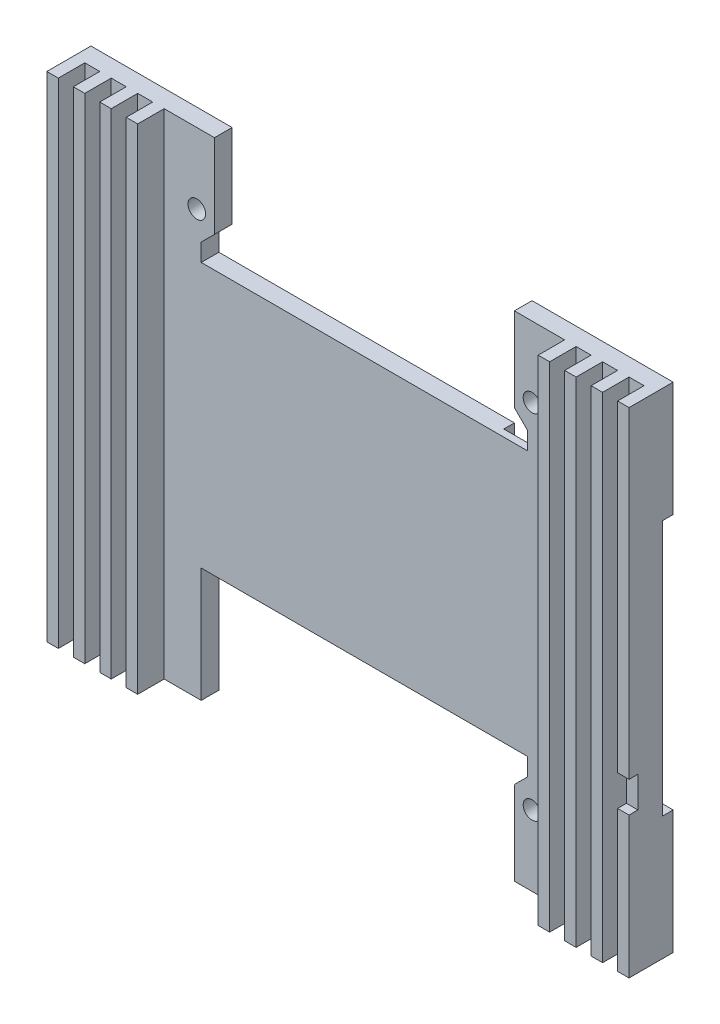
SolidWorks part; units mm, degrees
ref_plane "前视基准面" through (0, 0, 0) normal (0, 0, 1) x (1, 0, 0)
ref_plane "上视基准面" through (0, 0, 0) normal (0, 1, 0) x (1, 0, 0)
ref_plane "右视基准面" through (0, 0, 0) normal (1, 0, 0) x (0, 0, -1)
other "Configuration Table"
sketch "草图1" plane through (0, 0, 0) normal (0, 0, 1) x (1, 0, 0)
  line L0 (-18.5, 15) -> (18.5, 15)
  line L1 (18.5, 15) -> (18.5, 17)
  line L2 (18.5, 17) -> (17, 18.5)
  line L3 (17, 18.5) -> (17, 28)
  line L4 (17, 28) -> (33, 28)
  line L5 (33, 28) -> (33, -28)
  line L6 (33, -28) -> (17, -28)
  line L7 (17, -28) -> (17, -18.5)
  line L8 (17, -18.5) -> (18.5, -17)
  line L9 (18.5, -17) -> (18.5, -15)
  line L10 (18.5, -15) -> (-18.5, -15)
  line L11 (-18.5, -15) -> (-18.5, -17)
  line L12 (-18.5, -17) -> (-17, -18.5)
  line L13 (-17, -18.5) -> (-17, -28)
  line L14 (-17, -28) -> (-33, -28)
  line L15 (-33, -28) -> (-33, 28)
  line L16 (-33, 28) -> (-17, 28)
  line L17 (-17, 28) -> (-17, 18.5)
  line L18 (-17, 18.5) -> (-18.5, 17)
  line L19 (-18.5, 17) -> (-18.5, 15)
  line L20 (-34.3599, 0) -> (-7.4221, 0) construction
  line L21 (0, 36.2606) -> (0, 17.316) construction
  line L22 (-18.5, -17) -> (-18.5, -28)
  circle A0 centre (-19, 20) radius 1
  circle A1 centre (19, 20) radius 1
  circle A2 centre (19, -20) radius 1
  dimension "D9" = 2
  dimension "D1" = 30
  dimension "D2" = 40
  dimension "D3" = 66
  dimension "D4" = 38
  dimension "D5" = 37
  dimension "D6" = 34
  dimension "D7" = 28
  dimension "D8" = 2
extrude "凸台-拉伸1" add sketch "草图1" along normal blind 2 contours L22 L11 L10 L9 L8 L7 L6 L5 L4 L3 L2 L1 L0 L19 L18 L17 L16 L15 L14 A2 A1 A0
sketch "草图2" plane through (0, 0, 2) normal (0, 0, 1) x (1, 0, 0)
  line L1 (-33, -28) -> (-31.7, -28)
  line L2 (-33, -28) -> (-33, 28)
  line L3 (-33, 28) -> (-31.7, 28)
  line L4 (-31.7, -28) -> (-31.7, 28)
  line L6 (33, -28) -> (31.7, -28)
  line L7 (33, -28) -> (33, 28)
  line L8 (33, 28) -> (31.7, 28)
  line L9 (31.7, -28) -> (31.7, 28)
  line L10 (-30, -28) -> (-28.7, -28)
  line L11 (-30, -28) -> (-30, 28)
  line L12 (-30, 28) -> (-28.7, 28)
  line L13 (-28.7, -28) -> (-28.7, 28)
  line L14 (-27, -28) -> (-25.7, -28)
  line L15 (-27, -28) -> (-27, 28)
  line L16 (-27, 28) -> (-25.7, 28)
  line L17 (-25.7, -28) -> (-25.7, 28)
  line L18 (-24, -28) -> (-22.7, -28)
  line L19 (-24, -28) -> (-24, 28)
  line L20 (-24, 28) -> (-22.7, 28)
  line L21 (-22.7, -28) -> (-22.7, 28)
  line L22 (-33, -28) -> (-30, -28) construction
  line L23 (30, -28) -> (28.7, -28)
  line L24 (30, -28) -> (30, 28)
  line L25 (30, 28) -> (28.7, 28)
  line L26 (28.7, -28) -> (28.7, 28)
  line L27 (27, -28) -> (25.7, -28)
  line L28 (27, -28) -> (27, 28)
  line L29 (27, 28) -> (25.7, 28)
  line L30 (25.7, -28) -> (25.7, 28)
  line L31 (24, -28) -> (22.7, -28)
  line L32 (24, -28) -> (24, 28)
  line L33 (24, 28) -> (22.7, 28)
  line L34 (22.7, -28) -> (22.7, 28)
  line L35 (33, -28) -> (30, -28) construction
  dimension "D1" = 1.3
  dimension "D2" = 1.3
  dimension "D4" = 3
  dimension "D6" = 3
  dimension "D3" = 4
  dimension "D5" = 4
extrude "凸台-拉伸2" add sketch "草图2" along normal blind 3
sketch "草图3" plane through (0, 0, 0) normal (0, 0, -1) x (-1, 0, 0)
  line L0 (0, 21.7958) -> (0, 32.5445) construction
  line L1 (-10, -3) -> (10, -3)
  line L2 (-10, -3) -> (-10, 11)
  line L3 (-10, 11) -> (10, 11)
  line L4 (10, -3) -> (10, 11)
  line L5 (18.5, 15) -> (-18.5, 15) construction
  line L6 (-33, 28) -> (-33, -28) construction
  line L7 (-15, 15) -> (-33, 15)
  line L8 (-15, 15) -> (-15, -3)
  line L9 (-15, -3) -> (-33, -3)
  line L10 (-33, 15) -> (-33, -3)
  line L12 (-33, -3) -> (-23, -3)
  line L13 (-33, -3) -> (-33, -14)
  line L14 (-33, -14) -> (-23, -14)
  line L15 (-23, -3) -> (-23, -14)
  line M16 (18.5, 15) -> (-18.5, 15)
  line M21 (-33, 28) -> (-33, -28)
  dimension "D1" = 20
  dimension "D2" = 14
  dimension "D3" = 4
  dimension "D4" = 18
  dimension "D5" = 18
  dimension "D6" = 11
  dimension "D7" = 10
extrude "切除-拉伸1" cut sketch "草图3" against normal blind 1.2 contours L9 L8 L7 M16 M21 | L15 L9 L14 M21 | L1 L0 L3 L2 | L0 L1 L4 L3
sketch "草图4" plane through (0, 0, 5) normal (0, 0, 1) x (1, 0, 0)
  line L0 (31.7, 28) -> (31.7, -28) construction
  line L1 (31.7, -12) -> (33, -12)
  line L2 (31.7, -12) -> (31.7, -8.5)
  line L3 (31.7, -8.5) -> (33, -8.5)
  line L4 (33, -12) -> (33, -8.5)
  line L5 (33, -28) -> (33, 28) construction
  line L6 (31.7, -28) -> (33, -28) construction
  dimension "D1" = 16
  dimension "D2" = 3.5
extrude "切除-拉伸2" cut sketch "草图4" against normal blind 1
